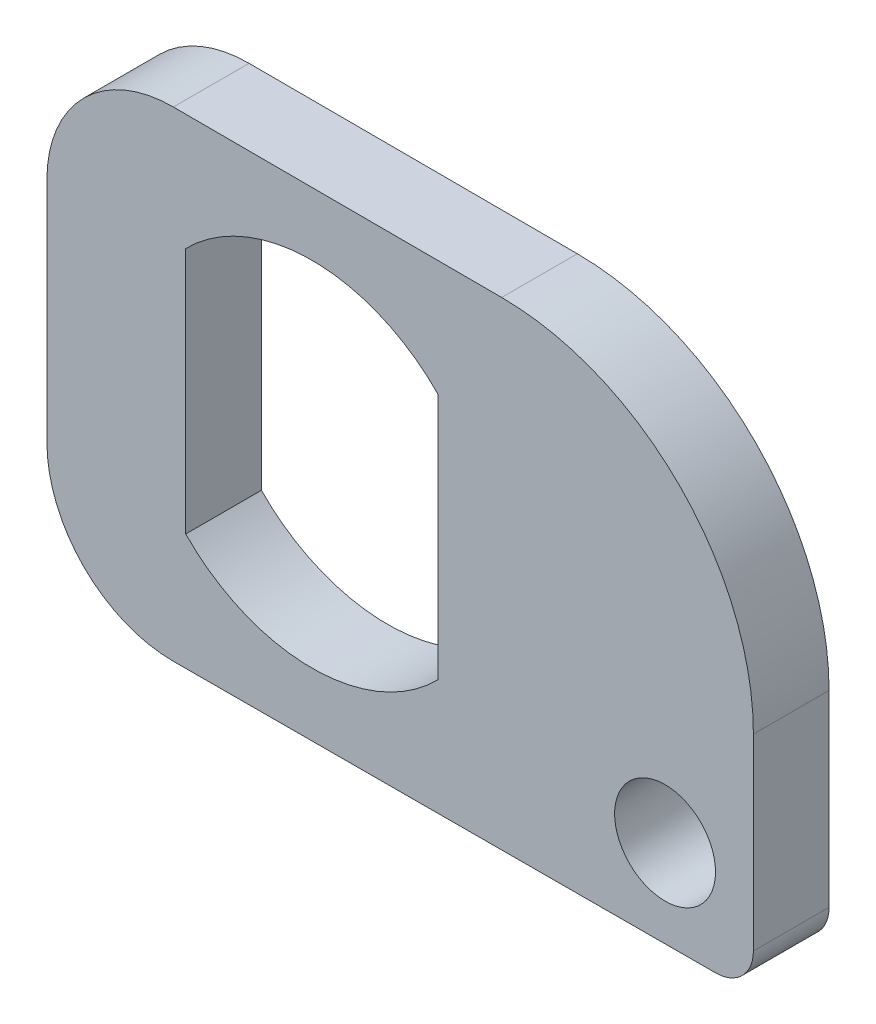
SolidWorks part; units mm, degrees
material "AISI 4340 Steel, normalized"
ref_plane "Front Plane" through (0, 0, 0) normal (0, 0, 1) x (1, 0, 0)
ref_plane "Top Plane" through (0, 0, 0) normal (0, 1, 0) x (1, 0, 0)
ref_plane "Right Plane" through (0, 0, 0) normal (1, 0, 0) x (0, 0, -1)
sketch "Sketch1" plane through (0, 0, 0) normal (0, 0, 1) x (1, 0, 0)
  line L4 (32.0071, -18.9239) -> (-10.9762, -19.0262)
  line L6 (0, 0) -> (0, 19.05) construction
  line L7 (-30, 19.05) -> (35, 19.05) construction
  line L8 (35, -1.0357) -> (35, -15.9239)
  line L9 (0, 0) -> (-24.6397, 0) construction
  line L11 (35, -19.05) -> (-21.4029, -19.05) construction
  line L12 (15.0476, 18.9643) -> (-10.9762, 19.0262)
  line L13 (-21, 9.0262) -> (-21, -9.0262)
  line L14 (-10, 9.798) -> (-10, -9.798)
  line L16 (10, 9.798) -> (10, -9.798)
  arc A0 (-10, -9.798) -> (10, -9.798) centre (0, 0) ccw
  arc A2 (10, 9.798) -> (-10, 9.798) centre (0, 0) ccw
  circle A3 centre (28, -12) radius 4
  arc A4 (-10.9762, -19.0262) -> (-21, -9.0262) centre (-11, -9.0262) cw
  arc A5 (-10.9762, 19.0262) -> (-21, 9.0262) centre (-11, 9.0262) ccw
  arc A6 (15.0476, 18.9643) -> (35, -1.0357) centre (15, -1.0357) cw
  arc A7 (32.0071, -18.9239) -> (35, -15.9239) centre (32, -15.9239) ccw
  point P3 (-21, 0)
  point P21 (-21, -19.05)
  point P24 (-21, 19.05)
  dimension "D1" = 28
  dimension "D2" = 28
  dimension "D4" = 21
  dimension "D7" = 8
  dimension "D9" = 10
  dimension "D10" = 20
  dimension "D11" = 3
  dimension "D3" = 12
  dimension "D5" = 19
  dimension "D6" = 20
  dimension "D8" = 56
extrude "Boss-Extrude1" add sketch "Sketch1" along normal blind 6
